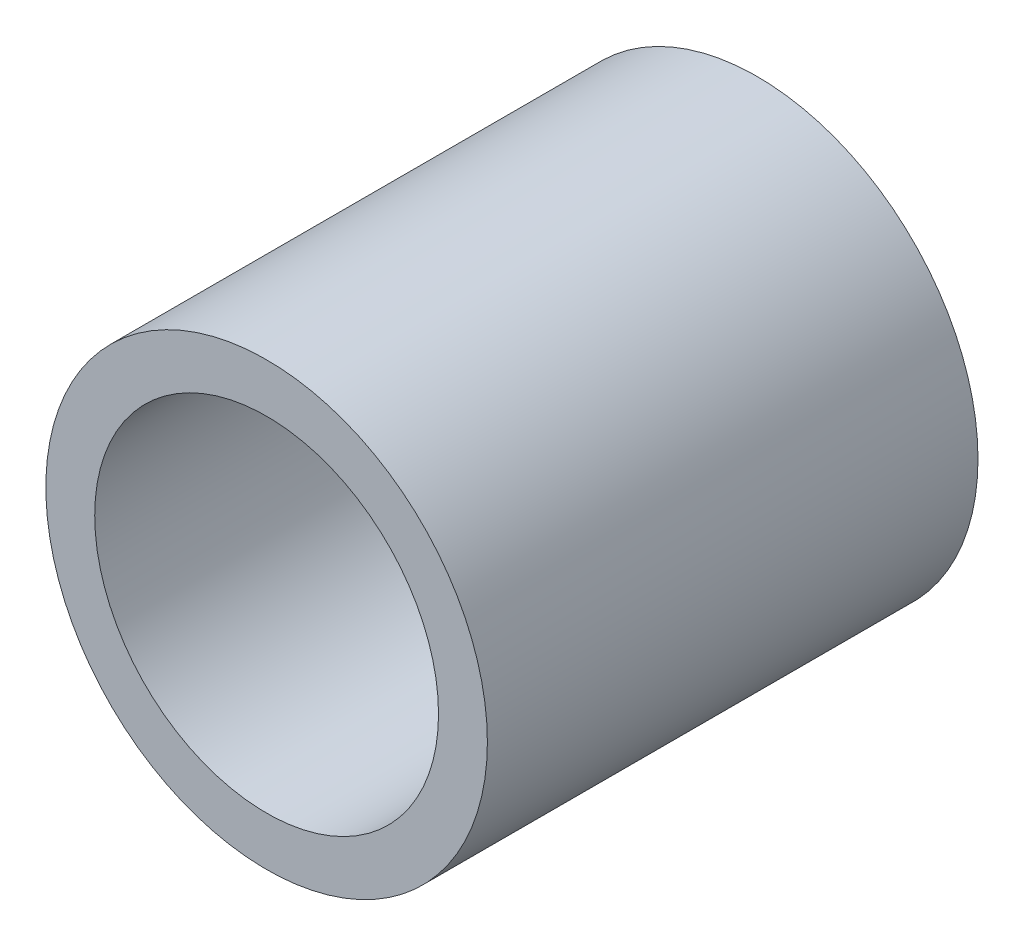
SolidWorks part; units mm, degrees
material "Commercial Bronze, UNS C22000 (90-10 Bronze)"
ref_plane "Front Plane" through (0, 0, 0) normal (0, 0, 1) x (1, 0, 0)
ref_plane "Top Plane" through (0, 0, 0) normal (0, 1, 0) x (1, 0, 0)
ref_plane "Right Plane" through (0, 0, 0) normal (1, 0, 0) x (0, 0, -1)
sketch "Sketch1" plane through (0, 0, 0) normal (0, 0, 1) x (1, 0, 0)
  circle A0 centre (0, 0) radius 7.1437
  circle A1 centre (0, 0) radius 5.5626
  dimension "D1" = 14.2875
  dimension "ID" = 11.1252
extrude "Extrude1" add sketch "Sketch1" along normal mid plane 15.875
sketch "Sketch2" plane through (0, 0, 0) normal (1, 0, 0) x (0, 0, -1)
  line L0 (-7.9375, -5.5626) -> (7.9375, -5.5626) construction
  line L3 (7.9375, 5.5626) -> (-7.9375, 5.5626) construction
  line L5 (-7.9375, -5.5626) -> (7.9375, -5.5626)
  line L6 (7.9375, 5.5626) -> (-7.9375, 5.5626)
sketch "Sketch4" plane through (0, 0, 7.9375) normal (0, 0, 1) x (1, 0, 0)
  line L0 (0, 0) -> (-3.9334, 3.9334)
  line L1 (0, -48.895) -> (0, 48.895) construction
  circle A0 centre (0, 0) radius 5.5626 construction
  dimension "D1" = 45
